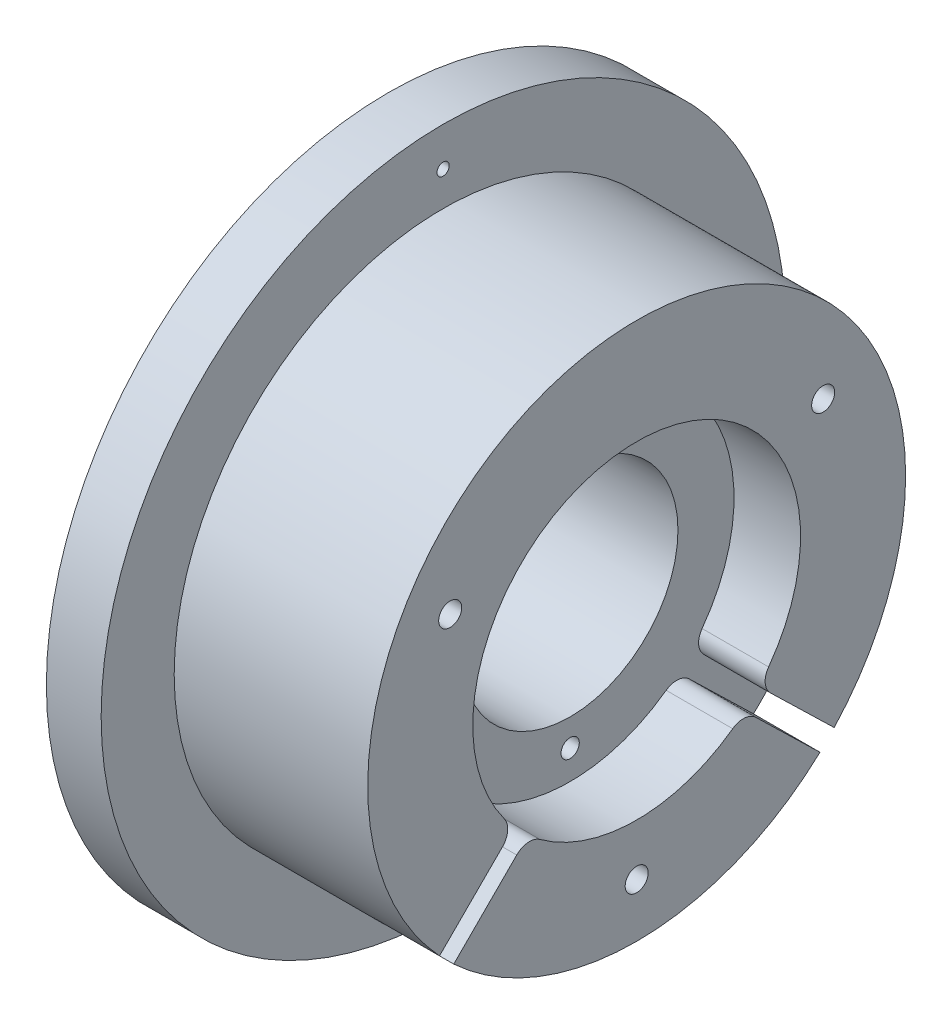
SolidWorks part; units mm, degrees
ref_plane "Front" through (0, 0, 0) normal (0, 0, 1) x (1, 0, 0)
ref_plane "Top" through (0, 0, 0) normal (0, 1, 0) x (1, 0, 0)
ref_plane "Right" through (0, 0, 0) normal (1, 0, 0) x (0, 0, -1)
sketch "Sketch1" plane through (0, 0, 0) normal (0, 0, 1) x (1, 0, 0)
  line L0 (0, 0) -> (0, 23.7871)
  line L1 (0, 23.7871) -> (3.81, 23.7871)
  line L2 (3.81, 23.7871) -> (3.81, 18.7071)
  line L3 (3.81, 18.7071) -> (17.272, 18.7071)
  line L4 (17.272, 18.7071) -> (17.272, 11.4)
  line L5 (17.272, 11.4) -> (12.645, 11.4)
  line L6 (12.645, 11.4) -> (12.645, 0)
  line L7 (12.645, 0) -> (0, 0)
  line L8 (12.645, 7.5) -> (0, 7.5)
  dimension "D1" = 23.7871
  dimension "D2" = 3.81
  dimension "D3" = 13.462
  dimension "D4" = 4.627
  dimension "D5" = 11.4
  dimension "D6" = 18.7071
  dimension "D7" = 7.5
revolve "Revolve1" add sketch "Sketch1" angle 360 about L7
sketch "Sketch2" plane through (17.272, 0, 0) normal (1, 0, 0) x (0, 0, -1)
  line L0 (0, 0) -> (-13.2279, -13.2279) construction
  line L1 (0, 0) -> (0, -18.7071) construction
  line L2 (0.3171, 0.3268) -> (13.7426, -12.7005)
  line L3 (-13.7229, -12.7329) -> (-12.7329, -13.7229)
  line L4 (-13.7229, -12.7329) -> (-0.495, 0.495)
  line L5 (-0.495, 0.495) -> (0.495, -0.495)
  line L6 (0.495, -0.495) -> (-12.7329, -13.7229)
  line L7 (12.7677, -13.7053) -> (13.7426, -12.7005)
  line L8 (12.7677, -13.7053) -> (-0.6578, -0.6779)
  line L9 (-0.6578, -0.6779) -> (0.3171, 0.3268)
  circle A0 centre (0, 0) radius 18.7071 construction
  circle A1 centre (-12.9709, 7.4887) radius 0.315
  circle A2 centre (12.9709, 7.4888) radius 0.315
  circle A3 centre (0, 0) radius 18.7071 construction
  circle A4 centre (0, -14.9775) radius 0.315
  point P6 (0, 0)
  point P14 (-13.2279, -13.2279)
  circle M8 centre (0, 0) radius 18.7071
  circle M9 centre (0, 0) radius 11.4
  dimension "D4" = 0.63
  dimension "D1" = 45
  dimension "D2" = 1.4
  dimension "D3" = 14.9775
  dimension "D5" = 3
  dimension "D6" = 2
extrude "Cut-Extrude1" cut sketch "Sketch2" against normal up to surface (4.627 mm away) contours L8 L9 L5 L4 L6 M9 | L6 L4 M9 M8 | L8 L2 M8 M9 | L9 L5 L6 L8 L2 M9 | A4 | A1 | A2 up to face at (12.645, 0, -7.5)
sketch "Sketch3" plane through (3.81, 0, 0) normal (1, 0, 0) x (0, 0, -1)
  line L0 (0, 0) -> (0, 21.082) construction
  circle A0 centre (0, 21.082) radius 0.425
  dimension "D1" = 0.85
  dimension "D2" = 21.082
extrude "Cut-Extrude2" cut sketch "Sketch3" against normal through all
sketch "Sketch4" plane through (12.645, 0, 0) normal (1, 0, 0) x (0, 0, -1)
  line L0 (0, -9.375) -> (0, 9.375) construction
  circle A0 centre (0, 9.375) radius 0.635
  circle A1 centre (0, -9.375) radius 0.635
  point P6 (0, 0)
  dimension "D2" = 1.27
  dimension "D1" = 18.75
extrude "Cut-Extrude3" cut sketch "Sketch4" against normal through all
fillet "Fillet1" radius 1.25 4 edges at (14.9585, -7.5508, 8.5408) (14.9585, -8.5408, 7.5508) (14.9585, -8.5894, -7.4955) (14.9585, -7.6056, -8.492)
hole_wizard "M2x0.4 Tapped Hole1" positions "3DSketch2" profile "Sketch5" tap size "M2x0.4" standard "ANSI Metric"
sketch3d "3DSketch2"
  line L0 (12.645, 7.4887, 12.9709) -> (17.272, 7.4887, 12.9709) construction
  line L1 (12.645, 7.4888, -12.9709) -> (17.272, 7.4888, -12.9709) construction
  line L2 (12.645, -14.9775, 0) -> (17.272, -14.9775, 0) construction
  point P0 (17.272, 7.4887, 12.9709)
  point P4 (17.272, 7.4888, -12.9709)
  point P8 (17.272, -14.9775, 0)
sketch "Sketch5" plane through (17.272, 7.4887, 12.9709) normal (0, 1, 0) x (0, 0, -1)
  line L0 (0, 0) -> (0, 6.8307)
  line L1 (0, 6.8307) -> (0.8, 6.35)
  line L2 (0.8, 6.35) -> (0.8, 0)
  line L5 (0.8, 0) -> (0, 0)
  line L10 (0, 6.8307) -> (-0.8, 6.35) construction
  line L11 (0, -6.35) -> (0, 107.95) construction
  dimension "Tap Drill Dia." = 1.6
  dimension "Tap Drill Depth" = 6.35
  dimension "Drill Angle" = 118
cosmetic thread "Hole Thread1" parameters "D1"=4, "D2"=2
cosmetic thread "Hole Thread2" parameters "D1"=4, "D2"=2
cosmetic thread "Hole Thread3" parameters "D1"=4, "D2"=2
